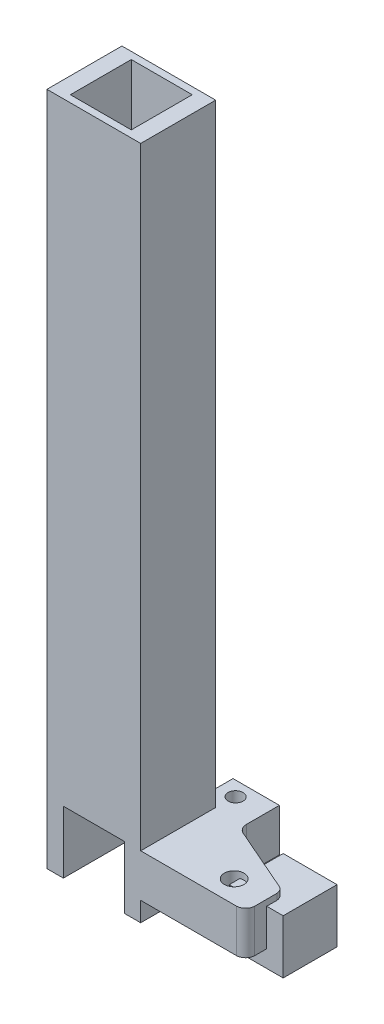
SolidWorks part; units mm, degrees
ref_plane "Front Plane" through (0, 0, 0) normal (0, 0, 1) x (1, 0, 0)
ref_plane "Top Plane" through (0, 0, 0) normal (0, 1, 0) x (1, 0, 0)
ref_plane "Right Plane" through (0, 0, 0) normal (1, 0, 0) x (0, 0, -1)
sketch "Sketch1" plane through (0, 0, 0) normal (0, 0, 1) x (1, 0, 0)
  line L1 (0, 0) -> (-11.5, 0)
  line L2 (0, 0) -> (0, -11.5)
  line L3 (0, -11.5) -> (-11.5, -11.5)
  line L4 (-11.5, 0) -> (-11.5, -11.5)
  dimension "D1" = 11.5
  dimension "D2" = 11.5
extrude "Boss-Extrude1" add sketch "Sketch1" along normal blind 11.5
sketch "Sketch2" plane through (0, 0, 0) normal (0, 0, 1) x (1, 0, 0)
  line L1 (-45.8982, -12) -> (-25.8982, -12)
  line L2 (-45.8982, -12) -> (-45.8982, 132)
  line L3 (-45.8982, 132) -> (-25.8982, 132)
  line L4 (-25.8982, -12) -> (-25.8982, 132)
  dimension "D1" = 20
  dimension "D2" = 144
extrude "Boss-Extrude2" add sketch "Sketch2" along normal blind 16 separate body
sketch "Sketch4" plane through (0, 132, 0) normal (0, 1, 0) x (1, 0, 0)
  line L0 (-25.8982, -16) -> (-25.8982, 0) construction
  line L1 (-42.3982, -1.5) -> (-29.3982, -1.5)
  line L2 (-42.3982, -1.5) -> (-42.3982, -14.5)
  line L3 (-42.3982, -14.5) -> (-29.3982, -14.5)
  line L4 (-29.3982, -1.5) -> (-29.3982, -14.5)
  line L5 (-45.8982, -16) -> (-45.8982, 0) construction
  line L6 (-25.8982, -16) -> (-45.8982, -16) construction
  line L7 (-25.8982, 0) -> (-45.8982, 0) construction
  dimension "D1" = 3.5
  dimension "D2" = 3.5
  dimension "D3" = 1.5
  dimension "D4" = 1.5
extrude "Cut-Extrude1" cut sketch "Sketch4" against normal through all contours L2 L1 L4 L3
sketch "Sketch5" plane through (0, 0, 16) normal (0, 0, 1) x (1, 0, 0)
  line L0 (-25.8982, -12) -> (-25.8982, 132) construction
  line L1 (-29.3982, 1.3) -> (-42.3982, 1.3)
  line L2 (-29.3982, 1.3) -> (-29.3982, -12)
  line L3 (-29.3982, -12) -> (-42.3982, -12)
  line L4 (-42.3982, 1.3) -> (-42.3982, -12)
  line L5 (-45.8982, 132) -> (-45.8982, -12) construction
  line L6 (-45.8982, -12) -> (-25.8982, -12) construction
  dimension "D1" = 3.5
  dimension "D2" = 3.5
  dimension "D3" = 0
  dimension "D4" = 13.3
extrude "Cut-Extrude2" cut sketch "Sketch5" against normal blind 1.5 contours L2 L1 L4 L3
sketch "Sketch6" plane through (0, 0, 0) normal (0, 0, -1) x (-1, 0, 0)
  line L0 (45.8982, -12) -> (25.8982, -12) construction
  line L1 (42.3982, -4) -> (29.3982, -4)
  line L2 (42.3982, -4) -> (42.3982, -12)
  line L3 (42.3982, -12) -> (29.3982, -12)
  line L4 (29.3982, -4) -> (29.3982, -12)
  line L5 (45.8982, 132) -> (45.8982, -12) construction
  line L6 (25.8982, -12) -> (25.8982, 132) construction
  dimension "D1" = 3.5
  dimension "D2" = 3.5
  dimension "D3" = 8
extrude "Cut-Extrude3" cut sketch "Sketch6" against normal blind 1.5 contours L2 L1 L4 L3
sketch "Sketch9" plane through (0, 0, 16) normal (0, 0, 1) x (1, 0, 0)
  line L0 (-35.8982, 132) -> (-35.8982, -17.9231) construction
  line L1 (-25.8982, 132) -> (-45.8982, 132) construction
ref_plane "Plane1" through (-35.8982, 0, 0) normal (-1, 0, 0) x (0, 0, 1)
sketch "Sketch10" plane through (-25.8982, 0, 0) normal (1, 0, 0) x (0, 0, -1)
  line L0 (0, -12) -> (0, 132) construction
  line L1 (-16, -12) -> (0, -12)
  line L2 (-16, -12) -> (-16, 1.3)
  line L3 (-16, 1.3) -> (0, 1.3)
  line L4 (0, -12) -> (0, 1.3)
  dimension "D1" = 13.3
extrude "Boss-Extrude3" add sketch "Sketch10" along normal blind 3.79
sketch "Sketch11" plane through (0, 0, 0) normal (0, 0, -1) x (-1, 0, 0)
  line L1 (29.3982, -12) -> (22.1082, -12)
  line L2 (29.3982, -12) -> (29.3982, 1.3)
  line L3 (29.3982, 1.3) -> (22.1082, 1.3)
  line L4 (22.1082, -12) -> (22.1082, 1.3)
extrude "Boss-Extrude4" add sketch "Sketch11" along normal blind 7.2
sketch "Sketch12" plane through (0, 1.3, 0) normal (0, 1, 0) x (1, 0, 0)
  line L0 (-29.3982, 7.2) -> (-22.1082, 7.2) construction
  line L1 (-29.3982, 7.2) -> (-29.3982, 0) construction
  circle A0 centre (-25.7532, 4.1) radius 1.6
  dimension "D1" = 3.2
  dimension "D2" = 3.1
  dimension "D3" = 3.645
extrude "Cut-Extrude4" cut sketch "Sketch12" against normal up to surface (13.3 mm away) up to face at (-25.7532, -12, 4.4)
sketch "Sketch13" plane through (0, 0, 16) normal (0, 0, 1) x (1, 0, 0)
  line L1 (-22.1082, -12) -> (-25.8982, -12)
  line L2 (-22.1082, -12) -> (-22.1082, -7.85)
  line L3 (-22.1082, -7.85) -> (-25.8982, -7.85)
  line L4 (-25.8982, -12) -> (-25.8982, -7.85)
  dimension "D1" = 3.79
  dimension "D2" = 4.15
extrude "Cut-Extrude6" cut sketch "Sketch13" against normal blind 16
sketch "Sketch15" plane through (-22.1082, 0, 0) normal (1, 0, 0) x (0, 0, -1)
  line L1 (0, -7.85) -> (7.2, -7.85)
  line L2 (0, -7.85) -> (0, -12)
  line L3 (0, -12) -> (7.2, -12)
  line L4 (7.2, -7.85) -> (7.2, -12)
extrude "Cut-Extrude7" cut sketch "Sketch15" against normal blind 16
sketch "Sketch17" plane through (-22.1082, 0, 0) normal (1, 0, 0) x (0, 0, -1)
  line L0 (0, -7.85) -> (-16, -7.85) construction
  line L1 (-16, 1.3) -> (0.6, 1.3)
  line L2 (-16, 1.3) -> (-16, -7.85)
  line L3 (-16, -7.85) -> (0.6, -7.85)
  line L4 (0.6, 1.3) -> (0.6, -7.85)
  dimension "D1" = 16.6
extrude "Boss-Extrude5" add sketch "Sketch17" along normal blind 18.6
sketch "Sketch18" plane through (0, 1.3, 0) normal (0, 1, 0) x (1, 0, 0)
  line L1 (-5.5032, -16) -> (-3.5082, -16)
  line L4 (-4.6117, -7.7631) -> (-18.215, -1.8117) construction
  line L5 (-3.5082, -16) -> (-3.5032, -14)
  line L9 (-3.5032, -14) -> (-3.5032, -9.458) construction
  line L10 (-21.5032, -16) -> (-5.5032, -16) construction
  line L11 (-4.6117, -7.7631) -> (-18.215, -1.8117)
  line L12 (-3.5032, -14) -> (-3.5032, -9.458)
  line L13 (-21.5032, -16) -> (-5.5032, -16)
  line L14 (-19.5032, 0.158) -> (-19.5032, 0.6)
  line L15 (-3.5082, 0.6) -> (-22.1082, 0.6) construction
  line L16 (-19.5032, 0.6) -> (-3.5082, 0.6)
  line L17 (-3.5082, 0.6) -> (-3.5032, -9.458)
  arc A3 (-19.5032, 0.158) -> (-18.215, -1.8117) centre (-17.3532, 0.158) ccw construction
  arc A4 (-3.5032, -9.458) -> (-4.6117, -7.7631) centre (-5.3532, -9.458) ccw construction
  arc A5 (-5.5032, -16) -> (-3.5032, -14) centre (-5.5032, -14) ccw construction
  arc A6 (-19.5032, 0.158) -> (-18.215, -1.8117) centre (-17.3532, 0.158) ccw
  arc A7 (-3.5032, -9.458) -> (-4.6117, -7.7631) centre (-5.3532, -9.458) ccw
  arc A8 (-5.5032, -16) -> (-3.5032, -14) centre (-5.5032, -14) ccw
  line M5 (-25.8982, -16) -> (-3.5082, -16)
  line M6 (-3.5082, -16) -> (-3.5082, 0.6)
  line M7 (-3.5082, 0.6) -> (-22.1082, 0.6)
extrude "Cut-Extrude10" cut sketch "Sketch18" against normal blind 18.6 contours A7 L14 A6 L11 M6 M7 | A8 M5 M6
sketch "Sketch22" plane through (0, 1.3, 0) normal (0, 1, 0) x (1, 0, 0)
  circle A1 centre (-10.7532, -11.2) radius 2.1 construction
  circle A2 centre (-10.7532, -11.2) radius 2.1
extrude "Cut-Extrude11" cut sketch "Sketch22" against normal blind 18.6 contours A2
sketch "Sketch24" plane through (0, 0, -0.6) normal (0, 0, -1) x (-1, 0, 0)
  line L1 (22.1082, -7.85) -> (19.5032, -7.85)
  line L2 (22.1082, -7.85) -> (22.1082, 1.3)
  line L3 (22.1082, 1.3) -> (19.5032, 1.3)
  line L4 (19.5032, -7.85) -> (19.5032, 1.3)
extrude "Boss-Extrude6" add sketch "Sketch24" along normal up to surface (6.6 mm away) up to face at (-25.7532, -3.275, -7.2)
